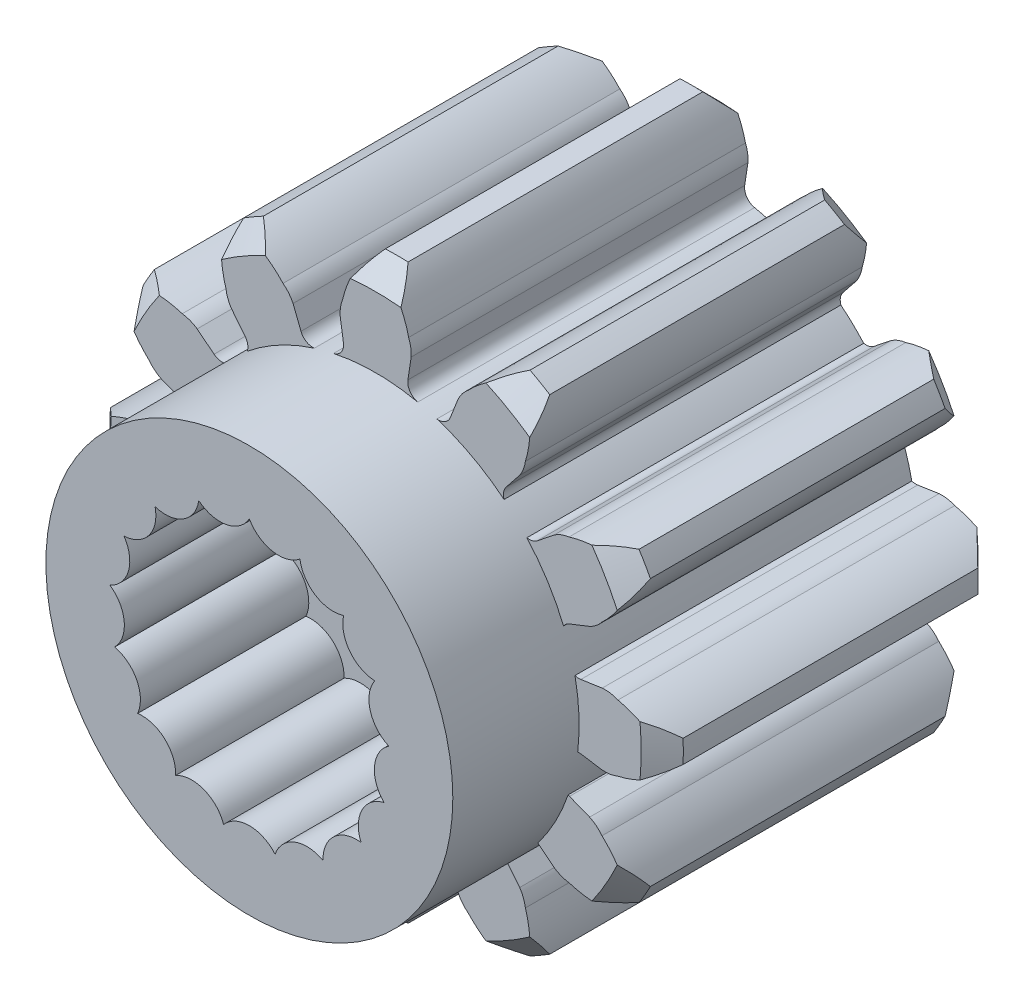
SolidWorks part; units mm, degrees
ref_plane "Front Plane" through (0, 0, 0) normal (0, 0, 1) x (1, 0, 0)
ref_plane "Top Plane" through (0, 0, 0) normal (0, 1, 0) x (1, 0, 0)
ref_plane "Right Plane" through (0, 0, 0) normal (1, 0, 0) x (0, 0, -1)
sketch "Sketch1" plane through (0, 0, 0) normal (0, 0, 1) x (1, 0, 0)
  circle A0 centre (0, 0) radius 4.833
  dimension "Di" = 9.666
extrude "Boss-Extrude1" add sketch "Sketch1" along normal blind 8
sketch "Sketch2" plane through (0, 0, 8) normal (0, 0, 1) x (1, 0, 0)
  line L0 (0, 0) -> (0, 64.154) construction
  line L2 (0.7658, 5.0667) -> (0.8426, 5.5748)
  line L3 (-0.7658, 5.0667) -> (-0.8426, 5.5748)
  line L4 (0.7658, 5.0667) -> (0, 0) construction
  arc A1 (0.0304, 6.7848) -> (0.0304, 6.7848) centre (0, 6) cw construction
  arc A8 (-0.2704, 6.9948) -> (0.2704, 6.9948) centre (0, 0) cw
  circle A9 centre (0, 0) radius 4.833
  arc A11 (1.0004, 4.7283) -> (-1.0004, 4.7283) centre (0, 0) ccw
  arc A17 (0.7287, 6.7627) -> (0.7391, 6.7634) centre (0.7837, 5.9486) ccw construction
  arc A18 (0.7837, 5.9486) -> (0.8426, 5.5748) centre (0.0291, 5.6381) cw
  arc A19 (-1.7749, 5.729) -> (-1.7753, 5.7338) centre (0.7837, 5.9486) ccw construction
  arc A21 (-1.4791, 5.8148) -> (2.2317, 5.5695) centre (0, 0) cw construction
  arc A22 (-4.249, 3.7061) -> (3.5637, 4.369) centre (0, 0) cw construction
  arc A23 (0.7837, 5.9486) -> (0.2704, 6.9948) centre (-1.7182, 5.37) ccw
  arc A24 (1.0004, 4.7283) -> (0.7658, 5.0667) centre (1.0625, 5.0218) cw
  arc A25 (-1.0004, 4.7283) -> (-0.7658, 5.0667) centre (-1.0625, 5.0218) ccw
  arc A26 (-0.7837, 5.9486) -> (-0.8426, 5.5748) centre (-0.0291, 5.6381) ccw
  arc A27 (-0.7837, 5.9486) -> (-0.2704, 6.9948) centre (1.7182, 5.37) cw
  dimension "CT" = 5.6382
  dimension "Dp" = 6
  dimension "De" = 7
  dimension "e" = 0.7854
  dimension "R1" = 0.816
  dimension "R2" = 2.568
  dimension "D2" = 0.3
  dimension "D1" = 0
sketch "Sketch3" plane through (0, 0, 8) normal (0, 0, 1) x (1, 0, 0)
  line L0 (0, 0) -> (335.0525, 5.0373) construction
  point P3 (174.1457, 3.6183)
  point P4 (212.24, 23.1932)
  point P5 (254.7104, 15.8308)
  dimension "M" = 1
  dimension "angulo de presion" = 20
  dimension "Z" = 12
extrude "Boss-Extrude2" add sketch "Sketch2" against normal through all
chamfer "Chamfer1" distance 0.5 angle 45 2 edges at (0, 7, 8) (0, 7, 0)
pattern_circular "CirPattern2" count 12 over 360 about axis through (0, 0.1929, 0) along (0, 0, 1) of "Boss-Extrude2", "Chamfer1"
sketch "Sketch5" plane through (0, 0, 8) normal (0, 0, 1) x (1, 0, 0)
  circle A0 centre (0, 0) radius 4.833
extrude "Boss-Extrude3" add sketch "Sketch5" along normal blind 3
sketch "Sketch4" plane through (0, 0, 11) normal (0, 0, 1) x (1, 0, 0)
  line L1 (0, 3.325) -> (-1.2011, 3.1005) construction
  line L2 (-1.2011, 3.1005) -> (-2.24, 2.4572) construction
  line L3 (-2.24, 2.4572) -> (-2.9764, 1.4821) construction
  line L4 (-2.9764, 1.4821) -> (-3.3108, 0.3068) construction
  line L5 (-3.3108, 0.3068) -> (-3.1981, -0.9099) construction
  line L6 (-3.1981, -0.9099) -> (-2.6534, -2.0038) construction
  line L7 (-2.6534, -2.0038) -> (-1.7504, -2.827) construction
  line L8 (-1.7504, -2.827) -> (-0.611, -3.2684) construction
  line L9 (-0.611, -3.2684) -> (0.611, -3.2684) construction
  line L10 (0.611, -3.2684) -> (1.7504, -2.827) construction
  line L11 (1.7504, -2.827) -> (2.6534, -2.0038) construction
  line L12 (2.6534, -2.0038) -> (3.1981, -0.9099) construction
  line L13 (3.1981, -0.9099) -> (3.3108, 0.3068) construction
  line L14 (3.3108, 0.3068) -> (2.9764, 1.4821) construction
  line L15 (2.9764, 1.4821) -> (2.24, 2.4572) construction
  line L16 (2.24, 2.4572) -> (1.2011, 3.1005) construction
  line L17 (1.2011, 3.1005) -> (0, 3.325) construction
  circle A0 centre (0, 0) radius 3.325 construction
  arc A1 (-2.24, 2.4572) -> (-1.2011, 3.1005) centre (-1.9925, 3.2179) ccw
  arc A2 (-1.2011, 3.1005) -> (0, 3.325) centre (-0.6955, 3.7204) ccw
  arc A3 (0, 3.325) -> (1.2011, 3.1005) centre (0.6955, 3.7204) ccw
  arc A4 (1.2011, 3.1005) -> (2.24, 2.4572) centre (1.9925, 3.2179) ccw
  arc A5 (2.24, 2.4572) -> (2.9764, 1.4821) centre (3.0204, 2.2809) ccw
  arc A6 (2.9764, 1.4821) -> (3.3108, 0.3068) centre (3.6404, 1.0358) ccw
  arc A7 (3.3108, 0.3068) -> (3.1981, -0.9099) centre (3.7687, -0.3492) ccw
  arc A8 (3.1981, -0.9099) -> (2.6534, -2.0038) centre (3.388, -1.687) ccw
  arc A9 (2.6534, -2.0038) -> (1.7504, -2.827) centre (2.5498, -2.797) ccw
  arc A10 (1.7504, -2.827) -> (0.611, -3.2684) centre (1.3672, -3.5293) ccw
  arc A11 (0.611, -3.2684) -> (-0.611, -3.2684) centre (0, -3.7848) ccw
  arc A12 (-0.611, -3.2684) -> (-1.7504, -2.827) centre (-1.3672, -3.5293) ccw
  arc A13 (-1.7504, -2.827) -> (-2.6534, -2.0038) centre (-2.5498, -2.797) ccw
  arc A14 (-2.6534, -2.0038) -> (-3.1981, -0.9099) centre (-3.388, -1.687) ccw
  arc A15 (-3.1981, -0.9099) -> (-3.3108, 0.3068) centre (-3.7687, -0.3492) ccw
  arc A16 (-3.3108, 0.3068) -> (-2.9764, 1.4821) centre (-3.6404, 1.0358) ccw
  arc A17 (-2.9764, 1.4821) -> (-2.24, 2.4572) centre (-3.0204, 2.2809) ccw
  dimension "D1" = 6.65
  dimension "D2" = 0.8
  dimension "D3" = 17
extrude "Cut-Extrude2" cut sketch "Sketch4" against normal blind 4
equation "\"Di@Sketch1\" = 2 * \"Dp@Sketch2\" -  ( 2 * \"M@Sketch3\" * 1.167 ) "
equation "\"D1@Boss-Extrude1\" =  ( 2.15 * pi * \"M@Sketch3\" )  + 5"
equation "\"De@Sketch2\" = \"M@Sketch3\" *  ( \"Z@Sketch3\" + 2 )  / 2"
equation "\"Dp@Sketch2\" = \"M@Sketch3\" * \"Z@Sketch3\" / 2"
equation "\"CT@Sketch2\"=cos ( \"angulo de presion@Sketch3\" )  * \"Dp@Sketch2\""
equation "\"e@Sketch2\"=0.5*\"M@Sketch3\"*pi/2"
equation "\"R1@Sketch2\"=0.068*\"Dp@Sketch2\"*2"
equation "\"R2@Sketch2\"=0.2140*\"Dp@Sketch2\"*2"
equation "\"D2@Sketch2\"=0.3*\"M@Sketch3\""
equation "\"D1@CirPattern2\"=\"Z@Sketch3\""
